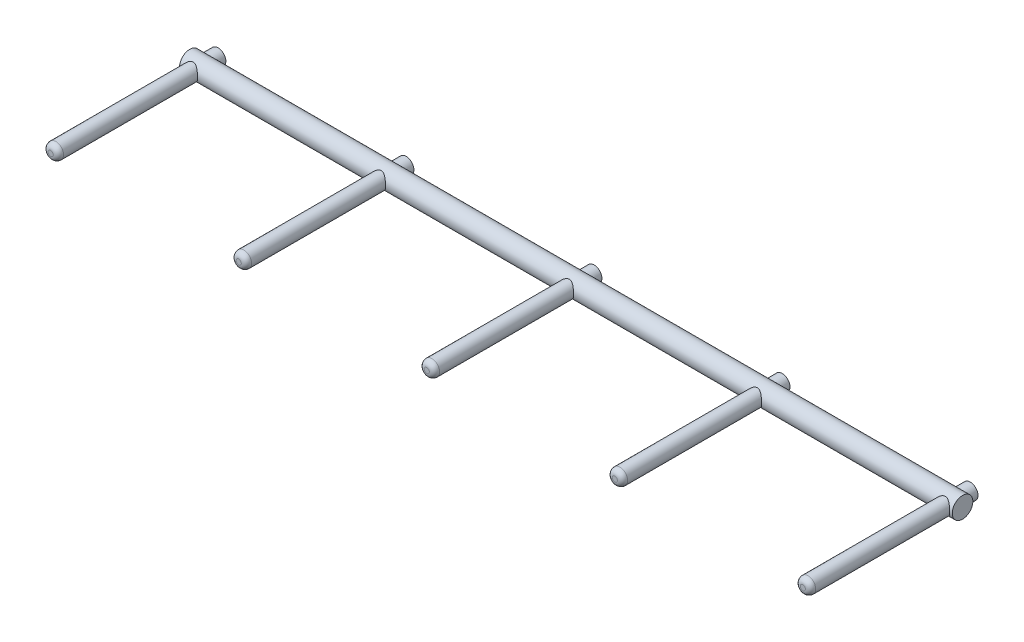
SolidWorks part; units mm, degrees
ref_plane "Front" through (0, 0, 0) normal (0, 0, 1) x (1, 0, 0)
ref_plane "Top" through (0, 0, 0) normal (0, 1, 0) x (1, 0, 0)
ref_plane "Right" through (0, 0, 0) normal (1, 0, 0) x (0, 0, -1)
sketch "Esquisse1" plane through (0, 0, 0) normal (1, 0, 0) x (0, 0, -1)
  circle A0 centre (0, 0) radius 4
  dimension "D1" = 8
extrude "Boss.-Extru.1" add sketch "Esquisse1" along normal mid plane 300
sketch "Esquisse3" plane through (0, 0, 0) normal (0, 0, 1) x (1, 0, 0)
  circle A0 centre (0, 0) radius 3
  dimension "D1" = 6
  dimension "D2" = 0
extrude "Boss.-Extru.3" add sketch "Esquisse3" along normal blind 65 from offset 7 separate body offset against normal yes
fillet "Congé1" radius 2 1 edges at (3, 0, 58)
pattern_linear "Répétition linéaire1" count 3 spacing 73 along (1, 0, 0) count 3 spacing 73 along (-1, 0, 0) of bodies 107 102
